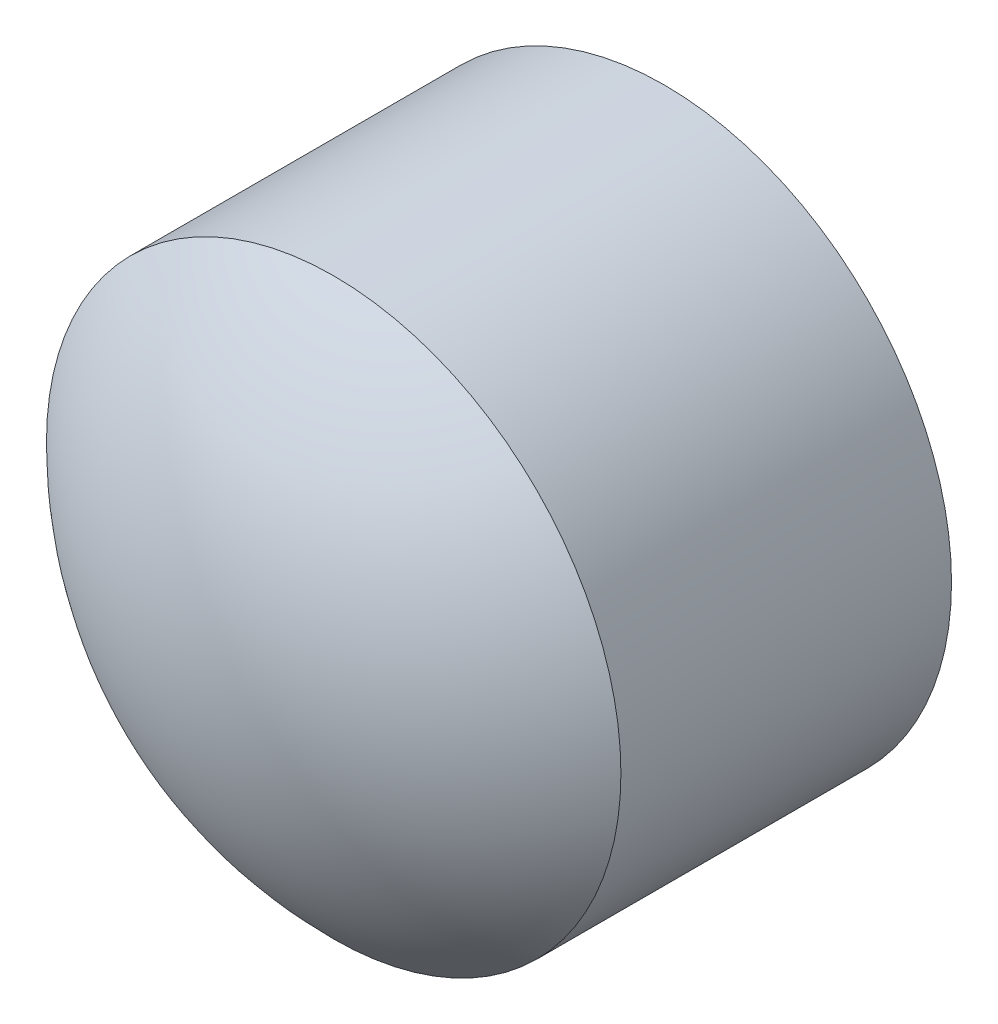
SolidWorks part; units mm, degrees
ref_plane "Plano frontal" through (0, 0, 0) normal (0, 0, 1) x (1, 0, 0)
ref_plane "Plano superior" through (0, 0, 0) normal (0, 1, 0) x (1, 0, 0)
ref_plane "Plano direito" through (0, 0, 0) normal (1, 0, 0) x (0, 0, -1)
sketch "Esboço1" plane through (0, 0, 0) normal (0, 0, 1) x (1, 0, 0)
  circle A0 centre (0, 0) radius 6.95
  dimension "D1" = 13.9
extrude "Ressalto-extrusão1" add sketch "Esboço1" along normal blind 8
sketch "Esboço2" plane through (0, 0, 8) normal (0, 0, 1) x (1, 0, 0)
  circle A0 centre (0, 0) radius 6.5
  dimension "D1" = 13
extrude "Corte-extrusão1" cut sketch "Esboço2" against normal blind 4
sketch "Esboço3" plane through (0, 0, 4) normal (0, 0, 1) x (1, 0, 0)
  circle A0 centre (0, 0) radius 5.5
  dimension "D1" = 11
extrude "Corte-extrusão2" cut sketch "Esboço3" against normal through all
sketch "Esboço4" plane through (0, 0, 0) normal (0, 1, 0) x (1, 0, 0)
  line L0 (-6.95, -8) -> (-6.5, -8)
  line L1 (-6.5, -8) -> (-6.5, -6.423)
  line L2 (-6.5, -4) -> (-6.5, -8) construction
  line L3 (-6.5, -6.423) -> (-4.0524, -6.423)
  line L4 (0, 0) -> (0, -11.6252) construction
  line L5 (0, -10.1023) -> (0, -10.8995)
  arc A0 (-6.95, -8) -> (0, -10.8995) centre (0, -1.1203) ccw
  arc A1 (-4.0524, -6.423) -> (0, -10.1023) centre (0, -6.0311) ccw
revolve "Revolução1" add sketch "Esboço4" angle 360 about L4
sketch "Esboço5" plane through (0, 0, 0) normal (0, 1, 0) x (1, 0, 0)
  line L0 (0, -10.8995) -> (0, 0) construction
  line L1 (-3.714, -5.4219) -> (-3.714, -6.0488)
  line L2 (4.0524, -6.423) -> (-4.0524, -6.423) construction
  line L3 (-3.714, -4.7949) -> (-3.0848, -4.7949)
  line L6 (0, -7.1537) -> (2.5614, -7.1537) construction
  line L7 (0, -6.423) -> (2.7648, -6.423) construction
  line L8 (-3.714, -5.4219) -> (-5.5, -5.4219)
  line L9 (-5.5, -5.4219) -> (-5.5, -3.7211)
  line L10 (-5.5, 0) -> (-5.5, -4) construction
  line L11 (-5.5, -3.7211) -> (-3.714, -3.7211)
  line L12 (-3.714, -3.7211) -> (-3.714, -4.7949)
  line L13 (0, -7.1537) -> (0, -6.423)
  arc A0 (-6.95, -8) -> (6.95, -8) centre (0, -1.1203) ccw construction
  arc A1 (-3.714, -6.0488) -> (0, -7.1537) centre (0, -0.3589) ccw
  arc A2 (-3.0848, -4.7949) -> (0, -6.423) centre (0, -2.6866) ccw
revolve "Revolução2" add sketch "Esboço5" angle 360 about L0
sketch "Esboço7" plane through (0, 0, 0) normal (0, 1, 0) x (1, 0, 0)
  line L0 (0, -10.8995) -> (0, 0) construction
  line L1 (-2.7354, -4.2637) -> (-2.7354, -3.2503)
  line L2 (-2.7354, -3.2503) -> (-5.5, -3.2503)
  line L3 (-5.5, 0) -> (-5.5, -3.7211) construction
  line L4 (-2.7354, -2.6057) -> (-5.5, -2.6057)
  line L5 (-5.5, -3.2503) -> (-5.5, -2.6057)
  line L6 (-2.7354, -2.6057) -> (-2.7354, -2.1452)
  line L7 (3.714, -3.7211) -> (-3.714, -3.7211) construction
  line L8 (0, -3.7211) -> (2.0139, -3.7211) construction
  line L9 (5.5, -3.7211) -> (-5.5, -3.7211) construction
  line L10 (0, -1.8851) -> (3.42, -1.8851) construction
  line L11 (0, -3.7211) -> (0, -1.8851)
  arc A0 (-6.95, -8) -> (6.95, -8) centre (0, -1.1203) ccw construction
  arc A1 (-2.7354, -4.2637) -> (0, -3.7211) centre (0, -10.8874) cw
  arc A2 (-2.7354, -2.1452) -> (0, -1.8851) centre (0, -16.4006) cw
revolve "Revolução3" add sketch "Esboço7" angle 360 about L0
